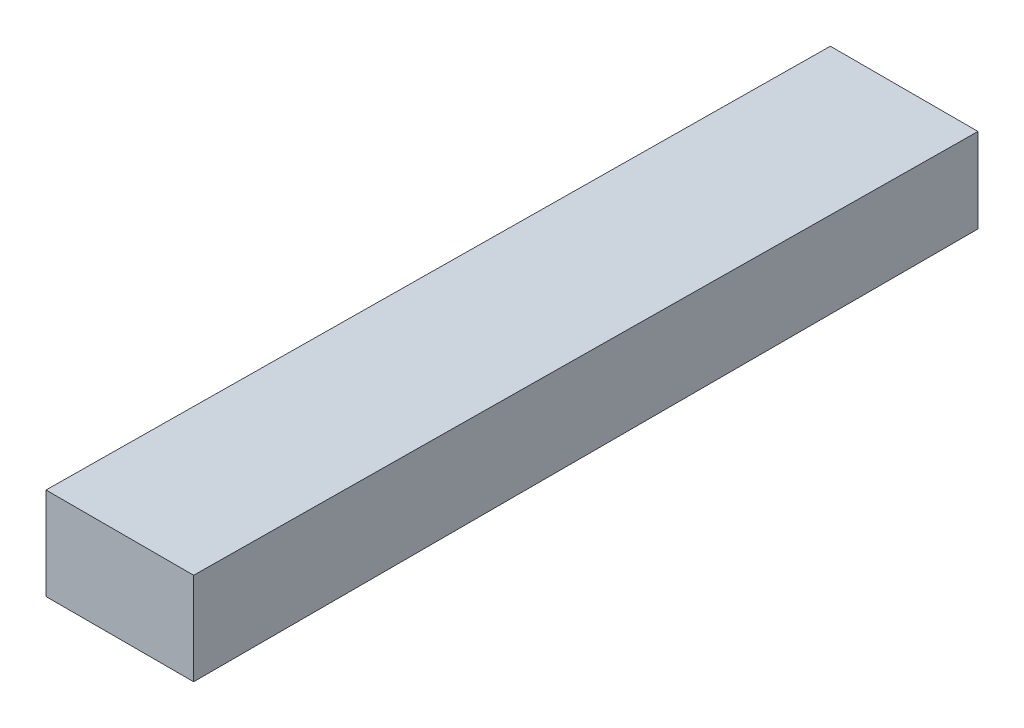
SolidWorks part; units mm, degrees
ref_plane "Front Plane" through (0, 0, 0) normal (0, 0, 1) x (1, 0, 0)
ref_plane "Top Plane" through (0, 0, 0) normal (0, 1, 0) x (1, 0, 0)
ref_plane "Right Plane" through (0, 0, 0) normal (1, 0, 0) x (0, 0, -1)
sketch "Sketch1" plane through (0, 0, 0) normal (0, 0, 1) x (1, 0, 0)
  line L1 (0, 0) -> (16, 0)
  line L2 (0, 0) -> (0, 10)
  line L3 (0, 10) -> (16, 10)
  line L4 (16, 0) -> (16, 10)
  dimension "D1" = 16
  dimension "D2" = 10
extrude "Boss-Extrude1" add sketch "Sketch1" along normal mid plane 85
sketch "Sketch3" plane through (0, 0, 0) normal (-1, 0, 0) x (0, 0, 1)
  line L0 (-42.5, 9.15) -> (42.5, 10)
  line L1 (-42.5, 10) -> (-42.5, 0) construction
  line L2 (-42.5, 9.15) -> (-42.5, 10)
  line L3 (-42.5, 10) -> (42.5, 10)
  dimension "D1" = 9.15
extrude "Cut-Extrude2" cut sketch "Sketch3" against normal blind 85
